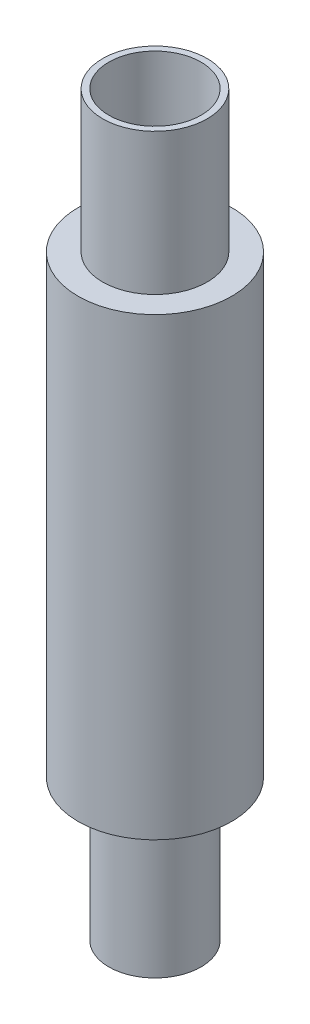
SolidWorks part; units mm, degrees
ref_plane "Front Plane" through (0, 0, 0) normal (0, 0, 1) x (1, 0, 0)
ref_plane "Top Plane" through (0, 0, 0) normal (0, 1, 0) x (1, 0, 0)
ref_plane "Right Plane" through (0, 0, 0) normal (1, 0, 0) x (0, 0, -1)
sketch "Sketch1" plane through (0, 0, 0) normal (0, 1, 0) x (1, 0, 0)
  circle A0 centre (0, 0) radius 7.5
  circle A1 centre (0, 0) radius 6.5
  dimension "D1" = 15
  dimension "D2" = 13
extrude "Boss-Extrude1" add sketch "Sketch1" along normal blind 23
sketch "Sketch2" plane through (0, 23, 0) normal (0, 1, 0) x (1, 0, 0)
  circle A0 centre (0, 0) radius 12.5
  circle A1 centre (0, 0) radius 6.5
  dimension "D1" = 25
  dimension "D2" = 13
extrude "Boss-Extrude2" add sketch "Sketch2" along normal blind 2
sketch "Sketch3" plane through (0, 25, 0) normal (0, 1, 0) x (1, 0, 0)
  circle A0 centre (0, 0) radius 12.5
  circle A1 centre (0, 0) radius 11
  dimension "D1" = 22
extrude "Boss-Extrude3" add sketch "Sketch3" along normal blind 70
sketch "Sketch4" plane through (0, 95, 0) normal (0, 1, 0) x (1, 0, 0)
  circle A0 centre (0, 0) radius 12.5
  circle A1 centre (0, 0) radius 7.5
  dimension "D1" = 15
extrude "Boss-Extrude4" add sketch "Sketch4" along normal blind 2
sketch "Sketch5" plane through (0, 97, 0) normal (0, 1, 0) x (1, 0, 0)
  circle A0 centre (0, 0) radius 8.5
  circle A1 centre (0, 0) radius 7.5
  dimension "D1" = 15
  dimension "D2" = 17
extrude "Boss-Extrude5" add sketch "Sketch5" along normal blind 23
